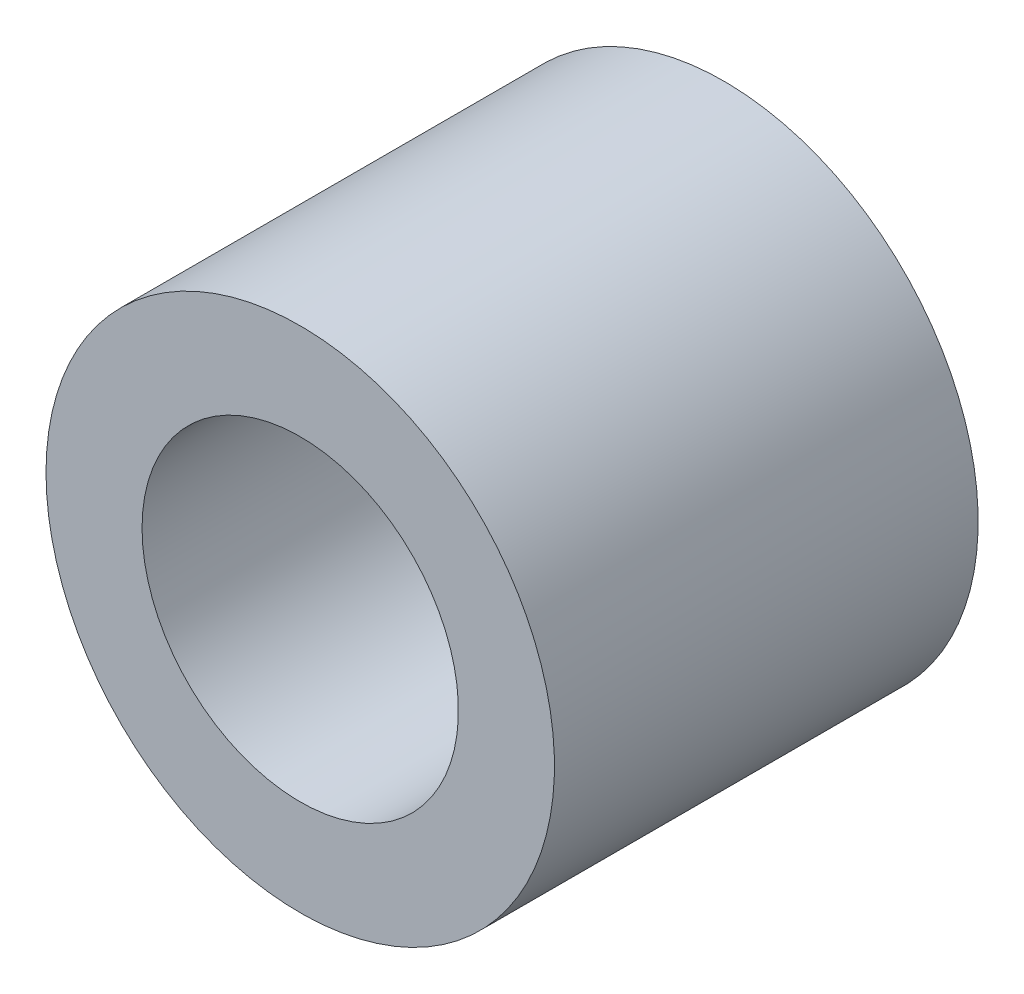
SolidWorks part; units mm, degrees
ref_plane "Front Plane" through (0, 0, 0) normal (0, 0, 1) x (1, 0, 0)
ref_plane "Top Plane" through (0, 0, 0) normal (0, 1, 0) x (1, 0, 0)
ref_plane "Right Plane" through (0, 0, 0) normal (1, 0, 0) x (0, 0, -1)
sketch "Sketch1" plane through (0, 0, 0) normal (0, 0, 1) x (1, 0, 0)
  circle A0 centre (0, 0) radius 5.715
  circle A1 centre (0, 0) radius 3.556
  dimension "D1" = 7.112
  dimension "D2" = 11.43
extrude "Boss-Extrude1" add sketch "Sketch1" along normal blind 9.525
